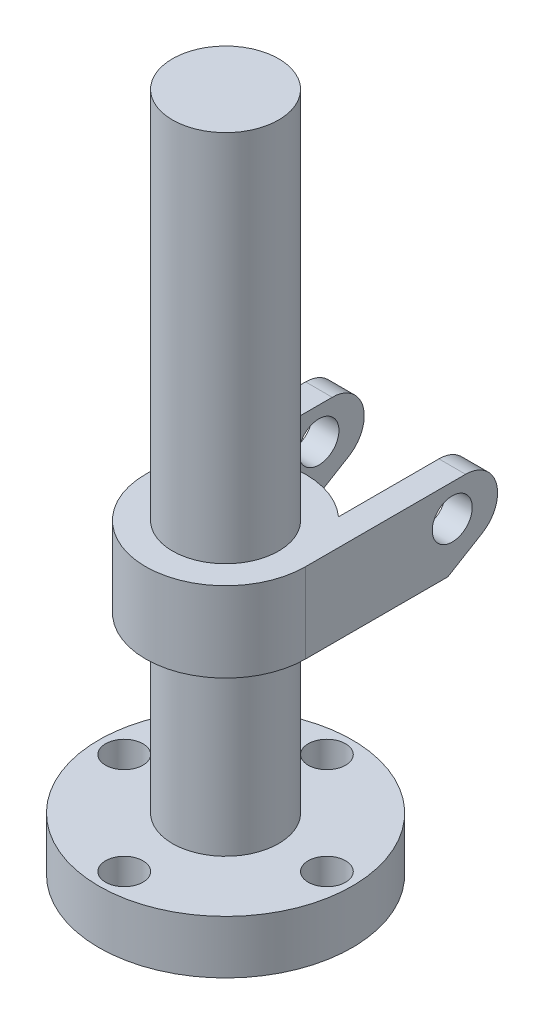
SolidWorks part; units mm, degrees
material "AISI 4340 Steel, normalized"
ref_plane "Front Plane" through (0, 0, 0) normal (0, 0, 1) x (1, 0, 0)
ref_plane "Top Plane" through (0, 0, 0) normal (0, 1, 0) x (1, 0, 0)
ref_plane "Right Plane" through (0, 0, 0) normal (1, 0, 0) x (0, 0, -1)
sketch "Sketch1" plane through (0, 0, 0) normal (0, 1, 0) x (1, 0, 0)
  circle A0 centre (0, 0) radius 47.5
  dimension "95" = 95
extrude "Boss-Extrude1" add sketch "Sketch1" along normal blind 20
sketch "Sketch2" plane through (0, 20, 0) normal (0, 1, 0) x (1, 0, 0)
  circle A0 centre (0, 0) radius 19.9
  dimension "D1" = 39.8
extrude "Boss-Extrude2" add sketch "Sketch2" along normal blind 65
sketch "Sketch3" plane through (0, 85, 0) normal (0, 1, 0) x (1, 0, 0)
  circle A0 centre (0, 0) radius 30
  dimension "D1" = 60
extrude "Boss-Extrude3" add sketch "Sketch3" along normal blind 30
sketch "Sketch4" plane through (0, 115, 0) normal (0, 1, 0) x (1, 0, 0)
  circle A0 centre (0, 0) radius 19.9
  dimension "D1" = 39.8
extrude "Boss-Extrude4" add sketch "Sketch4" along normal blind 140
ref_plane "Plane1" through (30, 0, 0) normal (1, 0, 0) x (0, 0, -1)
sketch "Sketch5" plane through (30, 0, 0) normal (1, 0, 0) x (0, 0, -1)
  line L0 (0, 115) -> (55, 115)
  line L1 (30, 115) -> (-30, 115) construction
  line L5 (55, 115) -> (60, 115)
  line L6 (66.1805, 92.714) -> (53.3422, 85)
  line L7 (0, 85) -> (53.3422, 85)
  line L8 (-19.9, 85) -> (19.9, 85) construction
  line L9 (0, 115) -> (0, 85)
  circle A0 centre (55, 103) radius 7.5
  arc A1 (66.1805, 92.714) -> (60, 115) centre (60, 103) ccw
  dimension "D3" = 15
  dimension "D5" = 12
  dimension "D1" = 55
  dimension "D2" = 14.9775
  dimension "D4" = 53.3422
  dimension "D6" = 31
  dimension "D7" = 18
  dimension "D8" = 12
  dimension "D9" = 12
other "AlignGroup1"
extrude "Boss-Extrude5" add sketch "Sketch5" against normal blind 10
mirror "Mirror1" about plane through (0, 0, 0) normal (1, 0, 0) of "Boss-Extrude5"
sketch "Sketch6" plane through (0, 20, 0) normal (0, 1, 0) x (1, 0, 0)
  circle A0 centre (0, 0) radius 38 construction
  circle A1 centre (0, 38) radius 7
  circle A2 centre (38, 0) radius 7
  circle A3 centre (0, -38) radius 7
  circle A4 centre (-38, 0) radius 7
  point P14 (0, 0)
  dimension "D1" = 76
  dimension "D2" = 14
  dimension "D3" = 4
extrude "Cut-Extrude1" cut sketch "Sketch6" against normal blind 10
sketch "Sketch7" plane through (0, 0, 0) normal (0, -1, 0) x (1, 0, 0)
  circle A0 centre (0, 0) radius 38 construction
  circle A1 centre (0, 38) radius 5
  circle A2 centre (38, 0) radius 5
  circle A3 centre (0, -38) radius 5
  circle A4 centre (-38, 0) radius 5
  point P14 (0, 0)
  dimension "D1" = 76
  dimension "D2" = 10
  dimension "D3" = 4
extrude "Cut-Extrude2" cut sketch "Sketch7" against normal blind 23
sketch "Sketch8" plane through (0, 0, 0) normal (0, -1, 0) x (1, 0, 0)
  circle A0 centre (0, 0) radius 20
  dimension "D1" = 40
extrude "Cut-Extrude3" cut sketch "Sketch8" against normal blind 15
